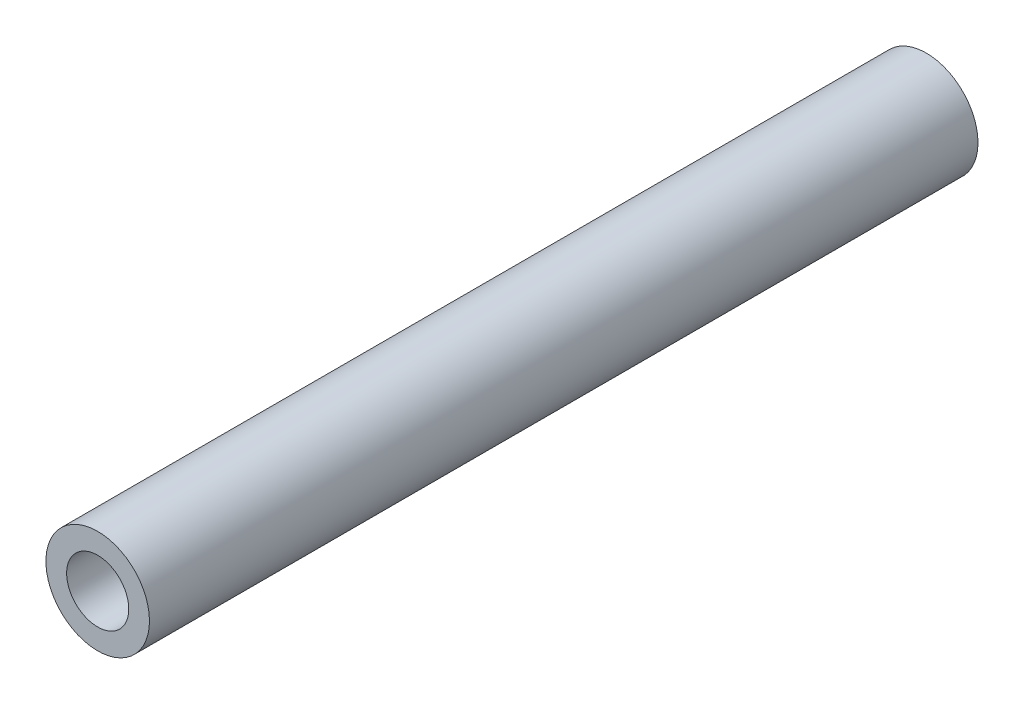
SolidWorks part; units mm, degrees
ref_plane "前视基准面" through (0, 0, 0) normal (0, 0, 1) x (1, 0, 0)
ref_plane "上视基准面" through (0, 0, 0) normal (0, 1, 0) x (1, 0, 0)
ref_plane "右视基准面" through (0, 0, 0) normal (1, 0, 0) x (0, 0, -1)
sketch "草图1" plane through (0, 0, 0) normal (0, 0, 1) x (1, 0, 0)
  circle A0 centre (0, 0) radius 2.5
  circle A1 centre (0, 0) radius 1.5
  dimension "D1" = 3
  dimension "D2" = 5
extrude "凸台-拉伸1" add sketch "草图1" along normal mid plane 40
